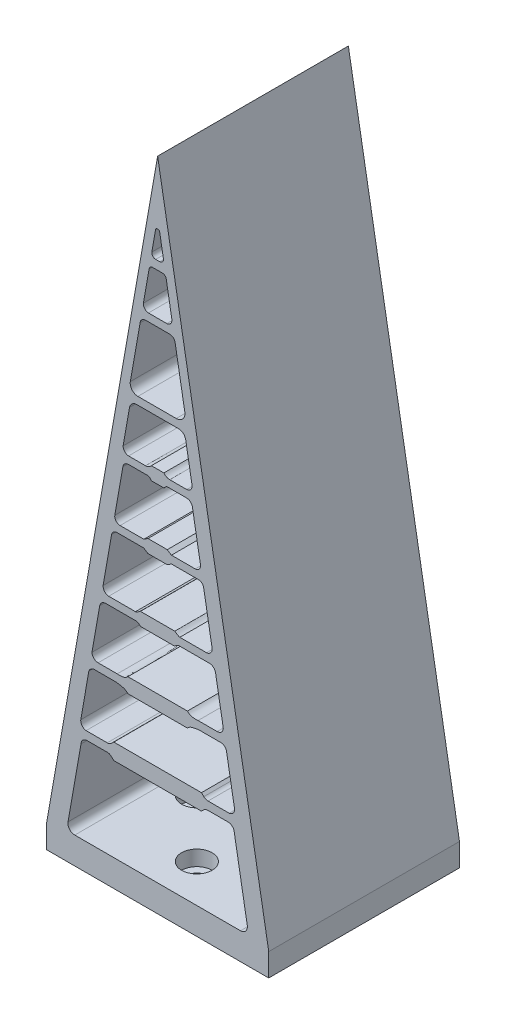
SolidWorks part; units mm, degrees
ref_plane "Front Plane" through (0, 0, 0) normal (0, 0, 1) x (1, 0, 0)
ref_plane "Top Plane" through (0, 0, 0) normal (0, 1, 0) x (1, 0, 0)
ref_plane "Right Plane" through (0, 0, 0) normal (1, 0, 0) x (0, 0, -1)
sketch "Sketch2" plane through (0, 0, 0) normal (0, 0, 1) x (1, 0, 0)
  line L0 (-3.8208, 5.7246) -> (-4.6594, 0.9441)
  line L1 (-2.8662, 6.5263) -> (-0.127, 6.5263)
  line L2 (-2.7294, 7.5263) -> (-0.1398, 7.5263)
  line L3 (-3.7226, 8.7089) -> (-2.4426, 16.0055)
  line L4 (10.2533, -0.2995) -> (-10.5329, -0.2995) construction
  line L5 (5.602, -35.391) -> (-5.8816, -35.391)
  line L6 (10.2924, -34.3417) -> (-10.572, -34.3417) construction
  line L7 (-6.7471, -34.8759) -> (-9.3776, -34.8759)
  line L8 (-10.1877, -35.6561) -> (-11.8885, -45.3515)
  line L10 (-6.7471, -33.8075) -> (-9.5203, -33.8075)
  line L11 (5.602, -33.2924) -> (-5.8816, -33.2924)
  line L12 (-5.8816, -35.391) -> (-6.1951, -35.0964)
  line L13 (-5.8816, -33.2924) -> (-6.1951, -33.587)
  line L14 (-10.2149, -32.9176) -> (-9.1547, -26.8736)
  line L15 (-0.1398, -46.407) -> (-0.1398, 36.0912)
  line L16 (10.7224, -46.407) -> (-11.002, -46.407)
  line L17 (-8.9517, -17.4599) -> (8.6721, -17.4599) construction
  line L18 (-8.7442, -24.5334) -> (-7.7284, -18.743)
  line L19 (3.747, -26.8821) -> (-4.0266, -26.8821)
  line L20 (-5.593, -26.3314) -> (-8.5363, -26.3314)
  line L21 (-5.4359, -25.3234) -> (-7.9442, -25.3234)
  line L22 (3.7621, -24.9476) -> (-4.0416, -24.9476)
  line L23 (2.1112, -18.4184) -> (-2.3908, -18.4184)
  line L24 (-3.0426, -18.0808) -> (-6.9815, -18.0808)
  line L25 (-3.0426, -17.0719) -> (-6.5572, -17.0719)
  line L26 (2.1112, -16.708) -> (-2.3908, -16.708)
  line L27 (-7.2858, -16.22) -> (-6.1735, -9.8795)
  line L28 (0.6806, -1.1682) -> (-0.9602, -1.1682)
  line L29 (-1.5427, -0.8139) -> (-3.9482, -0.8139)
  line L30 (-1.7258, 0.1541) -> (-3.9541, 0.1541)
  line L31 (0.6806, 0.5416) -> (-0.9602, 0.5416)
  line L32 (-1.6529, 16.6776) -> (1.3734, 16.6776)
  line L33 (1.0691, 17.6858) -> (-1.3487, 17.6858)
  line L34 (-2.0109, 18.4664) -> (-1.265, 22.719)
  line L35 (-0.4028, 24.2398) -> (0.1232, 24.2398)
  line L36 (-0.7725, 23.1326) -> (0.4929, 23.1326)
  line L37 (-0.0753, 27.808) -> (-0.2043, 27.808)
  line L38 (-0.4012, 27.6426) -> (-0.8953, 24.8262)
  line L39 (-0.1398, 36.0912) -> (-14.7017, -46.9196)
  line L40 (10.3358, -25.8908) -> (-10.6154, -25.8908) construction
  line L41 (-0.1398, 36.0912) -> (14.4222, -46.9196)
  line L42 (0.1217, 27.6426) -> (0.6157, 24.8262)
  line L43 (1.7314, 18.4664) -> (0.9854, 22.719)
  line L44 (1.4462, 0.1541) -> (3.6746, 0.1541)
  line L45 (1.2631, -0.8139) -> (3.6686, -0.8139)
  line L46 (7.0062, -16.22) -> (5.894, -9.8795)
  line L47 (2.763, -17.0719) -> (6.2776, -17.0719)
  line L48 (2.763, -18.0808) -> (6.7019, -18.0808)
  line L49 (5.1563, -25.3234) -> (7.6646, -25.3234)
  line L50 (5.3135, -26.3314) -> (8.2568, -26.3314)
  line L51 (8.4646, -24.5334) -> (7.4488, -18.743)
  line L52 (9.9353, -32.9176) -> (8.8751, -26.8736)
  line L53 (5.602, -33.2924) -> (5.9155, -33.587)
  line L54 (5.602, -35.391) -> (5.9155, -35.0964)
  line L55 (6.4675, -33.8075) -> (9.2408, -33.8075)
  line L57 (9.9081, -35.6561) -> (11.6089, -45.3515)
  line L58 (6.4675, -34.8759) -> (9.098, -34.8759)
  line L59 (3.443, 8.7089) -> (2.1631, 16.0055)
  line L60 (3.5412, 5.7246) -> (4.3798, 0.9441)
  line L61 (-4.0266, -26.8821) -> (-4.2618, -26.7001) construction
  line L62 (-4.2618, -26.7001) -> (-4.2983, -26.48) construction
  line L63 (-4.2983, -26.48) -> (-5.593, -26.3314) construction
  line L64 (-4.0416, -24.9476) -> (-4.2381, -25.1294) construction
  line L65 (-4.2381, -25.1294) -> (-4.4294, -25.3998) construction
  line L66 (-4.4294, -25.3998) -> (-5.4359, -25.3234) construction
  line L67 (-2.3908, -16.708) -> (-2.3818, -16.6274) construction
  line L68 (-2.3818, -16.6274) -> (-2.6292, -16.9728) construction
  line L69 (-2.6292, -16.9728) -> (-3.0426, -17.0719) construction
  line L70 (-2.3908, -18.4184) -> (-2.4207, -18.3905) construction
  line L71 (-2.4207, -18.3905) -> (-2.6757, -18.0592) construction
  line L72 (-2.6757, -18.0592) -> (-3.0426, -18.0808) construction
  line L73 (-0.9602, 0.5416) -> (-0.9826, 0.5215) construction
  line L74 (-0.9826, 0.5215) -> (-1.2369, 0.1499) construction
  line L75 (-1.2369, 0.1499) -> (-1.7258, 0.1541) construction
  line L76 (-0.9602, -1.1682) -> (-1.0604, -1.0614) construction
  line L77 (-1.0604, -1.0614) -> (-1.1978, -0.7909) construction
  line L78 (-1.1978, -0.7909) -> (-1.5427, -0.8139) construction
  line L79 (0.6806, -1.1682) -> (0.7808, -1.0614) construction
  line L80 (0.7808, -1.0614) -> (0.9182, -0.7909) construction
  line L81 (0.9182, -0.7909) -> (1.2631, -0.8139) construction
  line L82 (0.6806, 0.5416) -> (0.703, 0.5215) construction
  line L83 (0.703, 0.5215) -> (0.9573, 0.1499) construction
  line L84 (0.9573, 0.1499) -> (1.4462, 0.1541) construction
  line L85 (2.1112, -18.4184) -> (2.1411, -18.3905) construction
  line L86 (2.1411, -18.3905) -> (2.3961, -18.0592) construction
  line L87 (2.3961, -18.0592) -> (2.763, -18.0808) construction
  line L88 (2.1112, -16.708) -> (2.1023, -16.6274) construction
  line L89 (2.1023, -16.6274) -> (2.3496, -16.9728) construction
  line L90 (2.3496, -16.9728) -> (2.763, -17.0719) construction
  line L91 (3.7621, -24.9476) -> (3.9585, -25.1294) construction
  line L92 (3.9585, -25.1294) -> (4.1498, -25.3998) construction
  line L93 (4.1498, -25.3998) -> (5.1563, -25.3234) construction
  line L94 (3.747, -26.8821) -> (3.9822, -26.7001) construction
  line L95 (3.9822, -26.7001) -> (4.0187, -26.48) construction
  line L96 (4.0187, -26.48) -> (5.3135, -26.3314) construction
  line L97 (14.4222, -46.9196) -> (-0.1398, 36.0912)
  line L98 (2.2956, 7.5263) -> (-0.1398, 7.5263)
  line L102 (2.7316, 6.5263) -> (-0.127, 6.5263)
  line L104 (7.995, -8.8005) -> (-9.2456, -8.8005) construction
  line L105 (-1.9482, -8.3005) -> (-5.0631, -8.3005)
  line L106 (1.6686, -8.3005) -> (4.7835, -8.3005)
  line L107 (-5.4841, -9.3005) -> (-1.9482, -9.3005)
  line L108 (-5.7525, -7.4795) -> (-4.693, -1.4395)
  line L109 (5.4729, -7.4795) -> (4.4134, -1.4395)
  line L110 (1.6686, -8.3005) -> (1.1244, -7.945)
  line L111 (1.1244, -7.945) -> (-1.404, -7.945)
  line L112 (-1.404, -7.945) -> (-1.9482, -8.3005)
  line L113 (1.6686, -9.3005) -> (1.1244, -9.656)
  line L114 (1.1244, -9.656) -> (-1.404, -9.656)
  line L115 (-1.404, -9.656) -> (-1.9482, -9.3005)
  line L116 (1.6686, -9.3005) -> (5.2045, -9.3005)
  line L117 (14.4222, -49.9196) -> (-14.7017, -49.9196)
  line L118 (-14.7017, -49.9196) -> (-14.7017, -46.9196)
  line L119 (14.4222, -46.9196) -> (14.4222, -49.9196)
  arc A0 (-7.9442, -25.3234) -> (-8.7442, -24.5334) centre (-7.9442, -24.5234) cw
  arc A1 (-9.3776, -34.8759) -> (-10.1877, -35.6561) centre (-9.3776, -35.6866) ccw
  arc A2 (-7.7284, -18.743) -> (-6.9815, -18.0808) centre (-6.9267, -18.895) cw
  arc A3 (-6.5572, -17.0719) -> (-7.2858, -16.22) centre (-6.4956, -16.2816) cw
  arc A4 (-3.9482, -0.8139) -> (-4.693, -1.4395) centre (-3.9482, -1.5701) ccw
  arc A5 (-6.7471, -34.8759) -> (-6.1951, -35.0964) centre (-6.7151, -35.5973) cw
  arc A6 (-2.8662, 6.5263) -> (-3.8208, 5.7246) centre (-2.8662, 5.5571) ccw
  arc A7 (-3.9541, 0.1541) -> (-4.6594, 0.9441) centre (-3.9103, 0.903) cw
  arc A8 (-6.7471, -33.8075) -> (-6.1951, -33.587) centre (-6.7151, -33.0861) ccw
  arc A9 (-2.7294, 7.5263) -> (-3.7226, 8.7089) centre (-2.7294, 8.5347) cw
  arc A10 (-9.5203, -33.8075) -> (-10.2149, -32.9176) centre (-9.4227, -33.0152) cw
  arc A11 (-2.4426, 16.0055) -> (-1.6529, 16.6776) centre (-1.7118, 15.9467) cw
  arc A12 (-1.3487, 17.6858) -> (-2.0109, 18.4664) centre (-1.2902, 18.4067) cw
  arc A13 (-8.5363, -26.3314) -> (-9.1547, -26.8736) centre (-8.3785, -27.135) ccw
  arc A14 (-1.265, 22.719) -> (-0.7725, 23.1326) centre (-0.7725, 22.6326) cw
  arc A15 (0.9854, 22.719) -> (0.4929, 23.1326) centre (0.4929, 22.6326) ccw
  arc A16 (8.2568, -26.3314) -> (8.8751, -26.8736) centre (8.0989, -27.135) cw
  arc A17 (1.0691, 17.6858) -> (1.7314, 18.4664) centre (1.0106, 18.4067) ccw
  arc A18 (2.1631, 16.0055) -> (1.3734, 16.6776) centre (1.4322, 15.9467) ccw
  arc A19 (9.2408, -33.8075) -> (9.9353, -32.9176) centre (9.1431, -33.0152) ccw
  arc A21 (6.4675, -33.8075) -> (5.9155, -33.587) centre (6.4356, -33.0861) cw
  arc A22 (3.6746, 0.1541) -> (4.3798, 0.9441) centre (3.6307, 0.903) ccw
  arc A24 (6.4675, -34.8759) -> (5.9155, -35.0964) centre (6.4356, -35.5973) ccw
  arc A25 (3.6686, -0.8139) -> (4.4134, -1.4395) centre (3.6686, -1.5701) cw
  arc A26 (6.2776, -17.0719) -> (7.0062, -16.22) centre (6.216, -16.2816) ccw
  arc A27 (7.4488, -18.743) -> (6.7019, -18.0808) centre (6.6471, -18.895) ccw
  arc A28 (9.098, -34.8759) -> (9.9081, -35.6561) centre (9.098, -35.6866) cw
  arc A29 (7.6646, -25.3234) -> (8.4646, -24.5334) centre (7.6646, -24.5234) ccw
  arc A36 (-0.4028, 24.2398) -> (-0.8953, 24.8262) centre (-0.4028, 24.7398) cw
  arc A37 (0.1232, 24.2398) -> (0.6157, 24.8262) centre (0.1232, 24.7398) ccw
  arc A38 (-0.2043, 27.808) -> (-0.4012, 27.6426) centre (-0.2043, 27.608) ccw
  arc A39 (-0.0753, 27.808) -> (0.1217, 27.6426) centre (-0.0753, 27.608) cw
  arc A40 (3.443, 8.7089) -> (2.2956, 7.5263) centre (2.2956, 8.6743) cw
  arc A41 (3.5412, 5.7246) -> (2.7316, 6.5263) centre (2.5709, 5.5544) ccw
  arc A42 (-5.0631, -8.3005) -> (-5.7525, -7.4795) centre (-5.0631, -7.6005) cw
  arc A43 (-5.4841, -9.3005) -> (-6.1735, -9.8795) centre (-5.4841, -10.0005) ccw
  arc A44 (5.2045, -9.3005) -> (5.894, -9.8795) centre (5.2045, -10.0005) cw
  arc A45 (4.7835, -8.3005) -> (5.4729, -7.4795) centre (4.7835, -7.6005) ccw
  arc A46 (-11.8885, -45.3515) -> (-11.002, -46.407) centre (-11.002, -45.507) ccw
  arc A47 (11.6089, -45.3515) -> (10.7224, -46.407) centre (10.7224, -45.507) cw
  spline S0 degree 3 poles (-4.0266, -26.8821) (-4.2618, -26.7001) (-4.2983, -26.48) (-5.593, -26.3314) knots 0 0 0 0 1 1 1 1
  spline S1 degree 3 poles (-4.0416, -24.9476) (-4.2381, -25.1294) (-4.4294, -25.3998) (-5.4359, -25.3234) knots 0 0 0 0 1 1 1 1
  spline S2 degree 3 poles (-2.3908, -16.708) (-2.3818, -16.6274) (-2.6292, -16.9728) (-3.0426, -17.0719) knots 0 0 0 0 1 1 1 1
  spline S3 degree 3 poles (-2.3908, -18.4184) (-2.4207, -18.3905) (-2.6757, -18.0592) (-3.0426, -18.0808) knots 0 0 0 0 1 1 1 1
  spline S4 degree 3 poles (-0.9602, 0.5416) (-0.9826, 0.5215) (-1.2369, 0.1499) (-1.7258, 0.1541) knots 0 0 0 0 1 1 1 1
  spline S5 degree 3 poles (-0.9602, -1.1682) (-1.0604, -1.0614) (-1.1978, -0.7909) (-1.5427, -0.8139) knots 0 0 0 0 1 1 1 1
  spline S6 degree 3 poles (0.6806, -1.1682) (0.7808, -1.0614) (0.9182, -0.7909) (1.2631, -0.8139) knots 0 0 0 0 1 1 1 1
  spline S7 degree 3 poles (0.6806, 0.5416) (0.703, 0.5215) (0.9573, 0.1499) (1.4462, 0.1541) knots 0 0 0 0 1 1 1 1
  spline S8 degree 3 poles (2.1112, -18.4184) (2.1411, -18.3905) (2.3961, -18.0592) (2.763, -18.0808) knots 0 0 0 0 1 1 1 1
  spline S9 degree 3 poles (2.1112, -16.708) (2.1023, -16.6274) (2.3496, -16.9728) (2.763, -17.0719) knots 0 0 0 0 1 1 1 1
  spline S10 degree 3 poles (3.7621, -24.9476) (3.9585, -25.1294) (4.1498, -25.3998) (5.1563, -25.3234) knots 0 0 0 0 1 1 1 1
  spline S11 degree 3 poles (3.747, -26.8821) (3.9822, -26.7001) (4.0187, -26.48) (5.3135, -26.3314) knots 0 0 0 0 1 1 1 1
  point P2 (-0.1398, 16.6776)
  point P3 (-0.1398, -24.9476)
  point P7 (-0.1398, -18.4184)
  point P9 (-0.1398, 0.5416)
  point P10 (-0.1398, -16.708)
  point P11 (-0.1398, -1.1682)
  point P60 (-0.1398, -26.8821)
  point P73 (-0.1398, 24.2398)
  point P76 (-0.1398, 17.6858)
  point P78 (-0.1398, 23.1326)
  point P83 (-0.1398, -25.8908)
  point P85 (-0.1398, -17.4599)
  point P87 (-0.1398, -34.3417)
  point P88 (-0.1398, -0.2995)
  point P173 (-0.1398, 27.808)
  point P175 (-0.1398, -33.2924)
  point P176 (-0.1398, -35.391)
  point P189 (-5.8965, -8.3005)
  point P197 (5.617, -8.3005)
  point P204 (-0.9982, 24.2398)
  point P207 (0.7186, 24.2398)
  point P210 (-0.3722, 27.808)
  point P213 (0.0926, 27.808)
  point P217 (4.0652, -26.9742)
  point P218 (6.7851, -26.3314)
  point P221 (5.1997, -26.8439)
  dimension "D2" = 0.5
  dimension "D5" = 0.7983
  dimension "D3" = 0.2
  dimension "D4" = 0.5423
  dimension "D22" = 1.1826
  dimension "D23" = 0.8017
  dimension "D29" = 0.7
  dimension "D34" = 0.9
  dimension "D6" = 0.6183
  dimension "D7" = 0.79
  dimension "D8" = 0.7999
  dimension "D9" = 0.6622
  dimension "D10" = 0.7469
  dimension "D11" = 0.7286
  dimension "D12" = 0.8519
  dimension "D13" = 0.79
  dimension "D14" = 0.7052
  dimension "D15" = 0.6255
  dimension "D16" = 1.0089
  dimension "D17" = 1.008
  dimension "D18" = 0.7806
  dimension "D19" = 0.6622
  dimension "D20" = 0.7897
  dimension "D21" = 0.6721
  dimension "D24" = 1
  dimension "D25" = 2
  dimension "D26" = 2
  dimension "D27" = 2
  dimension "D28" = 1
  dimension "D30" = 2.5
  dimension "D31" = 0.7802
  dimension "D32" = 0.8101
  dimension "D33" = 3
extrude "Boss-Extrude1" add sketch "Sketch2" along normal blind 25
sketch "Sketch4" plane through (0, -49.9196, 0) normal (0, -1, 0) x (1, 0, 0)
  line L0 (0, 5) -> (0, 12.5) construction
  line L1 (-18.1003, 12.5) -> (18.2728, 12.5) construction
  line L2 (0, 29.8012) -> (0, -4.5912) construction
  line L4 (-14.7017, 25) -> (-14.7017, 0) construction
  circle A0 centre (0, 5) radius 1
  circle A1 centre (-7.5, 12.5) radius 1
  circle A2 centre (0, 20) radius 1
  circle A3 centre (7.5, 12.5) radius 1
  point P13 (0, 12.5)
  point P17 (-14.7017, 12.5)
  dimension "D1" = 2
  dimension "D2" = 7.5
  dimension "D3" = 4
extrude "Cut-Extrude1" cut sketch "Sketch4" against normal up to next
sketch "Sketch5" plane through (0, -46.407, 0) normal (0, 1, 0) x (1, 0, 0)
  circle A0 centre (7.5, -12.5) radius 1 construction
  circle A1 centre (-7.5, -12.5) radius 1 construction
  circle A2 centre (0, -20) radius 1 construction
  circle A3 centre (0, -5) radius 1 construction
  circle A4 centre (7.5, -12.5) radius 1
  circle A5 centre (-7.5, -12.5) radius 1
  circle A6 centre (0, -20) radius 1
  circle A7 centre (0, -5) radius 1
  circle A8 centre (0, -20) radius 2
  circle A9 centre (0, -5) radius 2
  circle A10 centre (-7.5, -12.5) radius 2
  circle A11 centre (7.5, -12.5) radius 2
  dimension "D2" = 4
  dimension "D1" = 4
  dimension "D3" = 4
  dimension "D4" = 4
extrude "Cut-Extrude2" cut sketch "Sketch5" against normal blind 2
